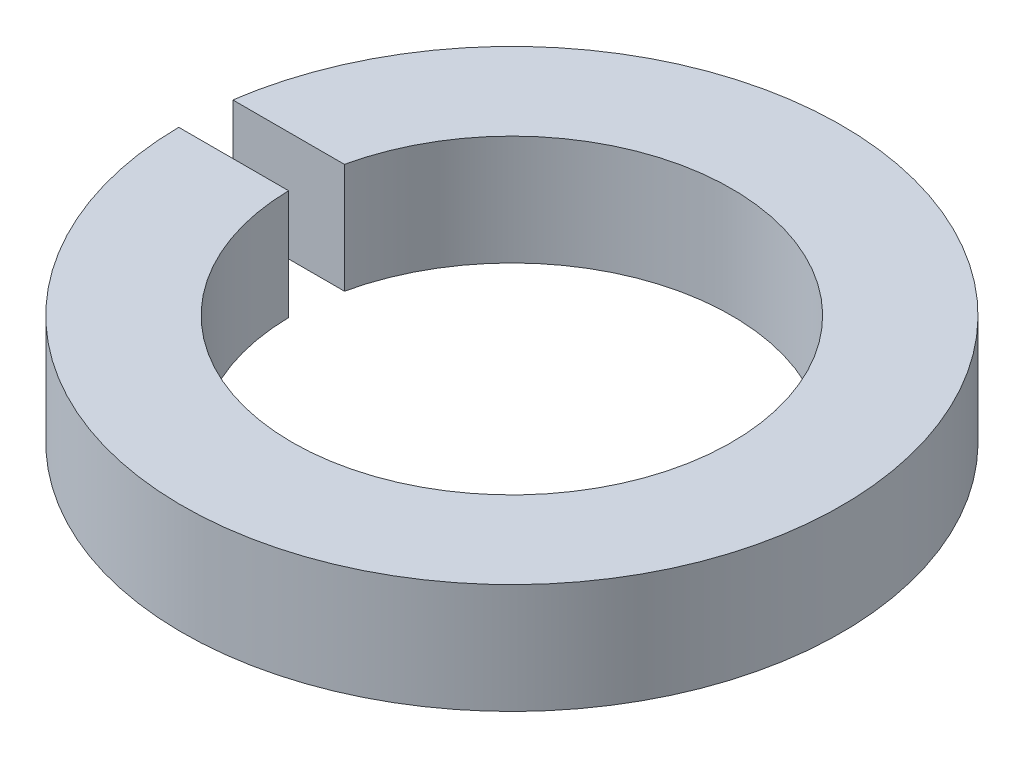
SolidWorks part; units mm, degrees
ref_plane "Alzado" through (0, 0, 0) normal (0, 0, 1) x (1, 0, 0)
ref_plane "Planta" through (0, 0, 0) normal (0, 1, 0) x (1, 0, 0)
ref_plane "Vista lateral" through (0, 0, 0) normal (1, 0, 0) x (0, 0, -1)
sketch "Croquis1" plane through (0, 0, 0) normal (0, 1, 0) x (1, 0, 0)
  circle A0 centre (0, 0) radius 3
  circle A1 centre (0, 0) radius 2
  dimension "D1" = 6
  dimension "D2" = 1
extrude "Extruir1" add sketch "Croquis1" along normal blind 1
sketch "Croquis2" plane through (0, 1, 0) normal (0, 1, 0) x (1, 0, 0)
  line L1 (-3.3333, -0.0325) -> (-1.3418, -0.0325)
  line L2 (-3.3333, -0.0325) -> (-3.3333, 0.4294)
  line L3 (-3.3333, 0.4294) -> (-1.3418, 0.4294)
  line L4 (-1.3418, -0.0325) -> (-1.3418, 0.4294)
extrude "Extruir2" cut sketch "Croquis2" against normal blind 10
